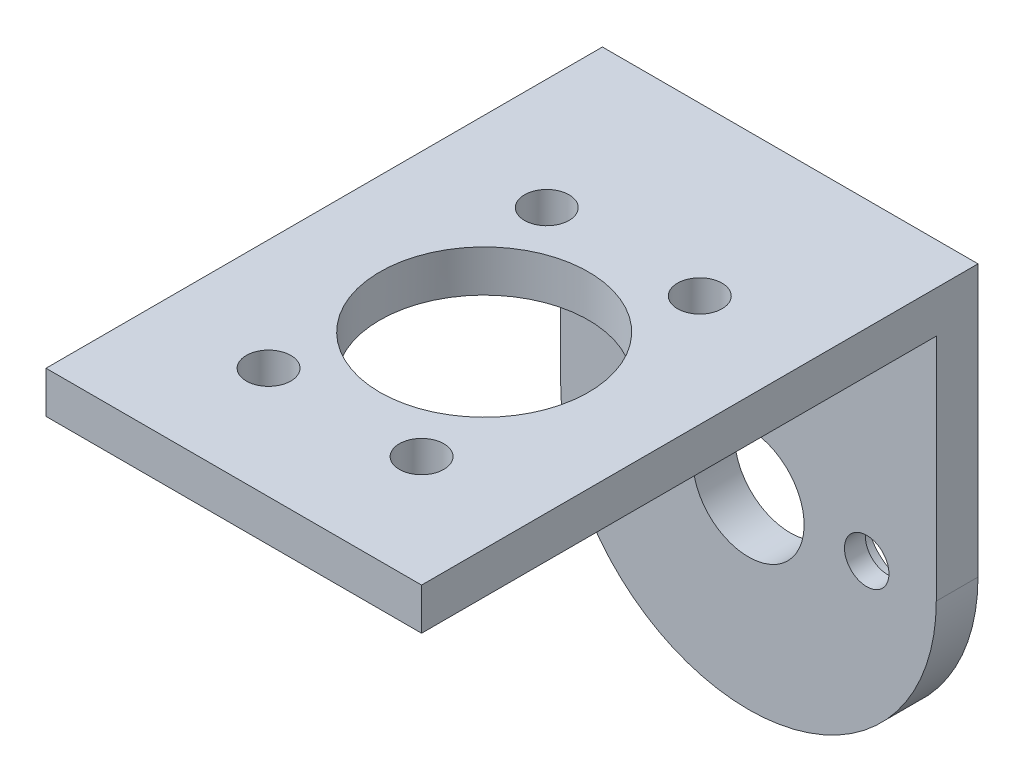
SolidWorks part; units mm, degrees
ref_plane "前视基准面" through (0, 0, 0) normal (0, 0, 1) x (1, 0, 0)
ref_plane "上视基准面" through (0, 0, 0) normal (0, 1, 0) x (1, 0, 0)
ref_plane "右视基准面" through (0, 0, 0) normal (1, 0, 0) x (0, 0, -1)
sketch "Model" plane through (0, 0, 0) normal (0, 0, 1) x (1, 0, 0)
  line L0 (2619.7667, 1592.8264) -> (2619.7667, 1612.3264)
  line L1 (2592.7667, 1592.8264) -> (2592.7667, 1612.3264)
  line L2 (2592.7667, 1612.3264) -> (2619.7667, 1612.3264)
  circle A0 centre (2606.2667, 1592.8264) radius 3.5
  arc A1 (2592.7667, 1592.8264) -> (2619.7667, 1592.8264) centre (2606.2667, 1592.8264) ccw
  dimension "D1" = 19.5
extrude "凸台-拉伸1" add sketch "Model" along normal blind 40
sketch "草图3" plane through (2619.7667, 0, 0) normal (1, 0, 0) x (0, 0, -1)
  line L0 (-40, 1592.8264) -> (-40, 1612.3264) construction
  line L1 (-40, 1609.3264) -> (-3, 1609.3264)
  line L2 (-40, 1609.3264) -> (-40, 1572.3264)
  line L3 (-40, 1572.3264) -> (-3, 1572.3264)
  line L4 (-3, 1609.3264) -> (-3, 1572.3264)
  line L5 (-40, 1612.3264) -> (0, 1612.3264) construction
  line L6 (0, 1592.8264) -> (0, 1612.3264) construction
  dimension "D1" = 3
  dimension "D2" = 3
  dimension "D3" = 40
extrude "切除-拉伸1" cut sketch "草图3" against normal blind 40
sketch "草图4" plane through (0, 1612.3264, 0) normal (0, 1, 0) x (1, 0, 0)
  line L6 (2619.7667, -40) -> (2619.7667, -32)
  circle A0 centre (2600.7667, -32) radius 1.5
  circle A1 centre (2611.7667, -32) radius 1.5
  circle A2 centre (2600.7667, -12) radius 1.5
  circle A3 centre (2611.7667, -12) radius 1.5
  dimension "D7" = 3
  dimension "D8" = 3
  dimension "D9" = 3
  dimension "D10" = 3
extrude "切除-拉伸2" cut sketch "草图4" against normal blind 40 contours A0 | A1 | A3 | A2
sketch "Sketch1" plane through (0, 0, 0) normal (0, 0, -1) x (-1, 0, 0)
  circle A0 centre (-2606.2667, 1592.8264) radius 4
extrude "Cut-Extrude1" cut sketch "Sketch1" against normal blind 10
sketch "Sketch2" plane through (0, 0, 0) normal (0, 0, -1) x (-1, 0, 0)
  circle A0 centre (-2614.7667, 1592.8264) radius 1.6
  circle A1 centre (-2597.7667, 1592.8264) radius 1.6
extrude "Cut-Extrude2" cut sketch "Sketch2" against normal blind 10
sketch "Sketch3" plane through (0, 0, 0) normal (0, 0, -1) x (-1, 0, 0)
  circle A0 centre (-2597.7667, 1592.8264) radius 3
  circle A1 centre (-2614.7667, 1592.8264) radius 3
extrude "Cut-Extrude3" cut sketch "Sketch3" against normal blind 1.5
sketch "Sketch4" plane through (0, 1612.3264, 0) normal (0, 1, 0) x (1, 0, 0)
  circle A0 centre (2600.7667, -12) radius 1.6
  circle A1 centre (2611.7667, -12) radius 1.6
  circle A2 centre (2600.7667, -32) radius 1.6
  circle A3 centre (2611.7667, -32) radius 1.6
extrude "Cut-Extrude4" cut sketch "Sketch4" against normal blind 10
sketch "Sketch5" plane through (0, 1612.3264, 0) normal (0, 1, 0) x (1, 0, 0)
  circle A0 centre (2606.2667, -22) radius 7.5
extrude "Cut-Extrude5" cut sketch "Sketch5" against normal blind 10
